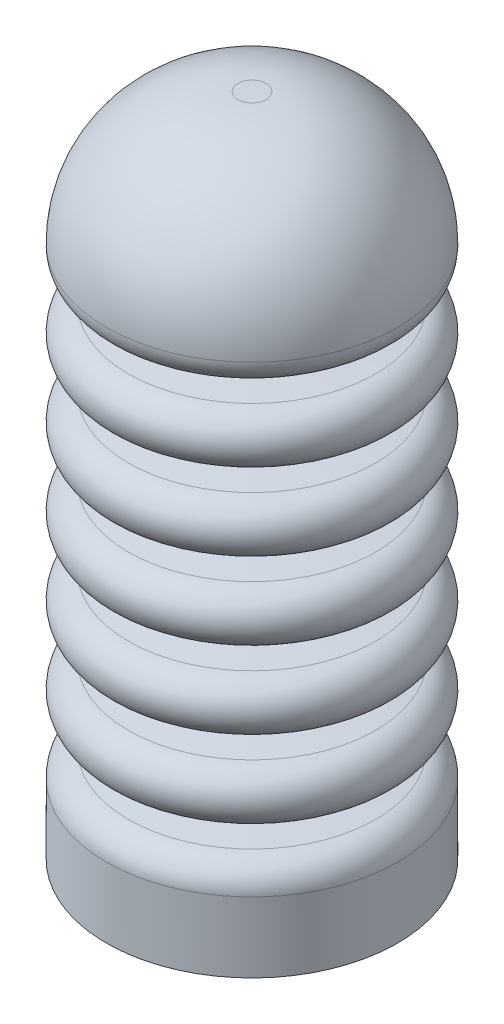
SolidWorks part; units mm, degrees
ref_plane "Front Plane" through (0, 0, 0) normal (0, 0, 1) x (1, 0, 0)
ref_plane "Top Plane" through (0, 0, 0) normal (0, 1, 0) x (1, 0, 0)
ref_plane "Right Plane" through (0, 0, 0) normal (1, 0, 0) x (0, 0, -1)
sketch "Sketch1" plane through (0, 0, 0) normal (1, 0, 0) x (0, 0, -1)
  line L0 (-9.6168, 62.5511) -> (-3.2517, 61.4898)
  line L3 (6, 85) -> (8, 85)
  line L4 (8, 83) -> (8, 85)
  line L5 (-10.7758, 0.25) -> (-12.75, 0.25)
  line L6 (-9.6168, 58.949) -> (-3.2517, 60.0102)
  line L7 (-2.9428, 52.4658) -> (-9.2826, 53.4748)
  line L9 (6, 83) -> (8, 83)
  line L10 (8, 83) -> (8, 85)
  line L11 (8, 83) -> (8, 0) construction
  line L13 (-9.6168, 40.5511) -> (-3.2517, 39.4898)
  line L14 (-9.6168, 51.5511) -> (-3.2517, 50.4898)
  line L15 (-9.6167, 47.949) -> (-3.2517, 49.0102)
  line L16 (-9.6167, 36.949) -> (-3.2517, 38.0102)
  line L17 (-9.6168, 29.5511) -> (-3.2517, 28.4898)
  line L18 (-9.6168, 18.5511) -> (-3.2517, 17.4898)
  line L19 (-9.6167, 14.949) -> (-3.2517, 16.0102)
  line L20 (-9.6168, 7.5511) -> (-3.2517, 6.4898)
  line L21 (-9.6168, 3.949) -> (-3.2517, 5.0102)
  line L22 (-9.2878, 64.5239) -> (-2.9227, 63.4626)
  line L23 (-9.2676, 46.086) -> (-2.9674, 47.0304)
  line L24 (-9.2678, 42.4141) -> (-2.9227, 41.4626)
  line L25 (-9.2826, 35.0031) -> (-2.9336, 36.0357)
  line L26 (-9.2826, 31.4969) -> (-2.9336, 30.4643)
  line L27 (-9.6167, 25.949) -> (-3.2517, 27.0102)
  line L28 (-9.2826, 24.0031) -> (-2.9336, 25.0357)
  line L29 (-9.2826, 20.4969) -> (-2.9336, 19.4643)
  line L30 (-9.2826, 13.0031) -> (-2.9336, 14.0357)
  line L31 (-9.2826, 9.4969) -> (-2.9336, 8.4643)
  line L32 (-9.2825, 2.0031) -> (-2.9336, 3.0357)
  line L33 (-9.2825, 57.0252) -> (-2.9428, 58.0342)
  arc A0 (6, 85) -> (-12.75, 66.25) centre (6, 66.25) ccw
  arc A2 (-12.75, 66.25) -> (-9.6168, 62.5511) centre (-9, 66.25) ccw
  arc A4 (-9.6167, 47.949) -> (-9.6168, 40.5511) centre (-9, 44.25) ccw
  arc A5 (-9.6167, 36.949) -> (-9.6168, 29.5511) centre (-9, 33.25) ccw
  arc A6 (-9.6167, 25.949) -> (-9.6168, 18.5511) centre (-9, 22.25) ccw
  arc A7 (-9.6167, 14.949) -> (-9.6168, 7.5511) centre (-9, 11.25) ccw
  arc A8 (-2.9428, 58.0342) -> (-2.9227, 63.4626) centre (-3.375, 60.75) ccw
  arc A9 (-2.9674, 47.0304) -> (-2.9428, 52.4658) centre (-3.375, 49.75) ccw
  arc A10 (-2.9336, 36.0357) -> (-2.9227, 41.4626) centre (-3.375, 38.75) ccw
  arc A11 (-2.9336, 25.0357) -> (-2.9336, 30.4643) centre (-3.375, 27.75) ccw
  arc A12 (-2.9336, 14.0357) -> (-2.9336, 19.4643) centre (-3.375, 16.75) ccw
  arc A14 (-9.6167, 3.949) -> (-12.75, 0.25) centre (-9, 0.25) ccw
  arc A15 (-2.9336, 3.0357) -> (-2.9336, 8.4643) centre (-3.375, 5.75) ccw
  arc A16 (-10.75, 66.25) -> (-9.2878, 64.5239) centre (-9, 66.25) ccw
  arc A17 (-3.2517, 60.0102) -> (-3.2517, 61.4898) centre (-3.375, 60.75) ccw
  arc A18 (-9.2825, 57.0252) -> (-9.2826, 53.4748) centre (-9, 55.25) ccw
  arc A19 (-3.2517, 49.0102) -> (-3.2517, 50.4898) centre (-3.375, 49.75) ccw
  arc A20 (-9.2676, 46.086) -> (-9.2678, 42.4141) centre (-9, 44.25) ccw
  arc A21 (-3.2517, 38.0102) -> (-3.2517, 39.4898) centre (-3.375, 38.75) ccw
  arc A22 (-9.2826, 35.0031) -> (-9.2826, 31.4969) centre (-9, 33.25) ccw
  arc A23 (-3.2517, 27.0102) -> (-3.2517, 28.4898) centre (-3.375, 27.75) ccw
  arc A24 (-9.2826, 24.0031) -> (-9.2826, 20.4969) centre (-9, 22.25) ccw
  arc A25 (-3.2517, 16.0102) -> (-3.2517, 17.4898) centre (-3.375, 16.75) ccw
  arc A26 (-9.2826, 13.0031) -> (-9.2826, 9.4969) centre (-9, 11.25) ccw
  arc A27 (-3.2517, 5.0102) -> (-3.2517, 6.4898) centre (-3.375, 5.75) ccw
  arc A28 (-9.2825, 2.0031) -> (-10.7758, 0.25) centre (-9, 0.25) ccw
  arc A29 (6, 83) -> (-10.75, 66.25) centre (6, 66.25) ccw
  arc A32 (-9.6167, 58.949) -> (-9.6168, 51.5511) centre (-9, 55.25) ccw
  dimension "D4" = 18.75
  dimension "D6" = 7.5
  dimension "D11" = 11
  dimension "D13" = 5.5
  dimension "D21" = 2
  dimension "D22" = 2
  dimension "D7" = 11
  dimension "D8" = 11
  dimension "D9" = 11
  dimension "D10" = 11
  dimension "D12" = 11
  dimension "D15" = 11
  dimension "D16" = 11
  dimension "D17" = 11
  dimension "D18" = 11
  dimension "D19" = 11
revolve "Revolve2" add sketch "Sketch1" angle 360 about L11
sketch "Sketch2" plane through (0, 0.25, 0) normal (0, -1, 0) x (1, 0, 0)
  circle A0 centre (0, -8) radius 20.75
extrude "Boss-Extrude1" add sketch "Sketch2" along normal blind 10
